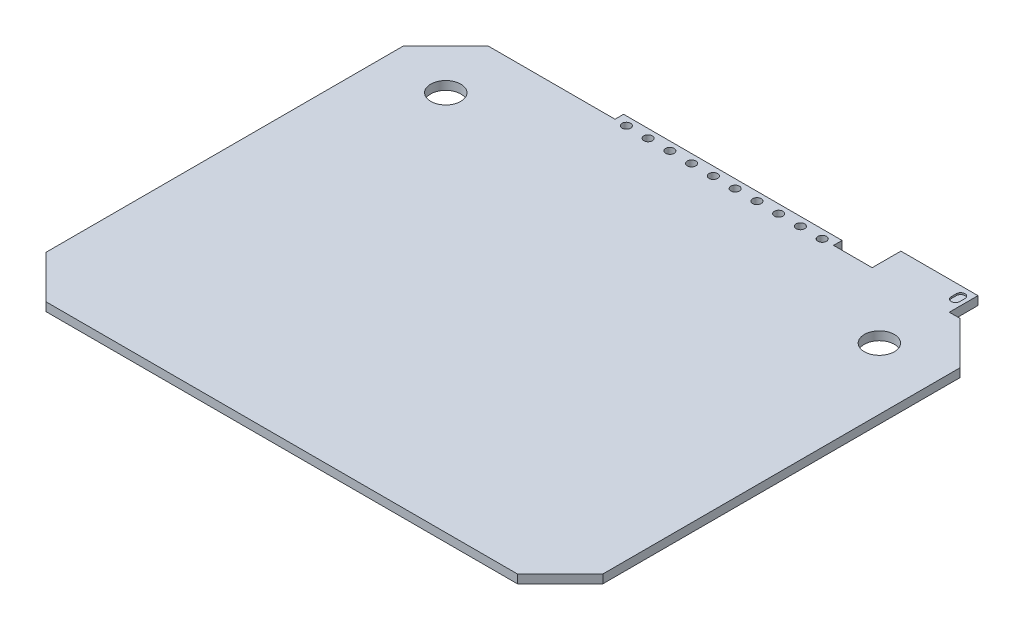
SolidWorks part; units mm, degrees
ref_plane "CL Y" through (0, 0, 0) normal (0, 0, 1) x (1, 0, 0)
ref_plane "PCBA Top" through (0, 0, 0) normal (0, 1, 0) x (1, 0, 0)
ref_plane "CL X" through (0, 0, 0) normal (1, 0, 0) x (0, 0, -1)
sketch "Sketch1" plane through (0, 0, 0) normal (0, 1, 0) x (1, 0, 0)
  line L0 (0, -50) -> (0, 50) construction
  line L1 (-32.5, 25.825) -> (32.5, 25.825)
  line L2 (-32.5, 25.825) -> (-32.5, -25.825)
  line L3 (-32.5, -25.825) -> (32.5, -25.825)
  line L4 (32.5, 25.825) -> (32.5, -25.825)
  line L5 (-50, 0) -> (50, 0) construction
  point P4 (0, 25.825)
  point P7 (32.5, 0)
  dimension "D1" = 65
  dimension "D2" = 51.65
extrude "Boss-Extrude1" add sketch "Sketch1" along normal blind 1
chamfer "Chamfer1" distance 5 angle 45 4 edges at (-32.5, 0.5, -25.825) (-32.5, 0.5, 25.825) (32.5, 0.5, -25.825) (32.5, 0.5, 25.825)
sketch "Sketch2" plane through (0, 0, 0) normal (0, 1, 0) x (1, 0, 0)
  line L0 (-25.3, 18.625) -> (25.3, 18.625) construction
  line L1 (0, -50) -> (0, 50) construction
  line L2 (27.5, 25.825) -> (-27.5, 25.825) construction
  circle A0 centre (-25.3, 18.625) radius 1.75
  circle A1 centre (25.3, 18.625) radius 1.75
  point P2 (0, 18.625)
  dimension "D3" = 3.5
  dimension "D1" = 7.2
  dimension "D2" = 50.6
extrude "Cut-Extrude2" cut sketch "Sketch2" along normal up to next
sketch "Sketch3" plane through (0, 1, 0) normal (0, 1, 0) x (1, 0, 0)
  line L0 (27.5, 25.825) -> (-27.5, 25.825) construction
  line L1 (-12.75, 26.825) -> (12.75, 26.825)
  line L2 (-12.75, 26.825) -> (-12.75, 25.825)
  line L3 (-12.75, 25.825) -> (12.75, 25.825)
  line L4 (12.75, 26.825) -> (12.75, 25.825)
  line L5 (0, -50) -> (0, 50) construction
  point P6 (0, 26.825)
  dimension "D1" = 25.5
  dimension "D2" = 1
extrude "Boss-Extrude3" add sketch "Sketch3" against normal up to surface (1 mm away) up to face at (-25.3, 0, -16.875)
sketch "Sketch4" plane through (0, 1, 0) normal (0, 1, 0) x (1, 0, 0)
  line L0 (-12.75, 25.825) -> (12.75, 25.825) construction
  line L1 (-1.27, 24.6659) -> (-1.27, 26.9841) construction
  line L2 (0, -50) -> (0, 50) construction
  circle A0 centre (-1.27, 25.825) radius 0.5
  dimension "D2" = 1
  dimension "D1" = 1.27
extrude "Cut-Extrude3" cut sketch "Sketch4" against normal up to next
pattern_linear "LPattern1" count 6 spacing 2.54 along (1, 0, 0) count 5 spacing 2.54 along (-1, 0, 0) of "Cut-Extrude3"
sketch "Sketch5" plane through (0, 1, 0) normal (0, 1, 0) x (1, 0, 0)
  line L0 (27.5, 25.825) -> (12.75, 25.825) construction
  line L1 (17.26, 29.175) -> (26.26, 29.175)
  line L2 (17.26, 29.175) -> (17.26, 25.825)
  line L3 (17.26, 25.825) -> (26.26, 25.825)
  line L4 (26.26, 29.175) -> (26.26, 25.825)
  line L6 (21.76, 29.175) -> (21.76, 35.5034) construction
  line L7 (0, -50) -> (0, 50) construction
  dimension "D1" = 9
  dimension "D2" = 3.35
  dimension "D3" = 21.76
extrude "Boss-Extrude4" add sketch "Sketch5" against normal up to surface (1 mm away) up to face at (11.43, 0, -25.325)
sketch "Sketch6" plane through (0, 1, 0) normal (0, 1, 0) x (1, 0, 0)
  line L0 (25.3, 28.115) -> (25.3, 27.515) construction
  line L1 (25.8, 28.115) -> (25.8, 27.515)
  line L2 (24.8, 28.115) -> (24.8, 27.515)
  line L3 (25.3, 18.625) -> (25.3, 31.5325) construction
  arc A0 (25.8, 28.115) -> (24.8, 28.115) centre (25.3, 28.115) ccw
  arc A1 (24.8, 27.515) -> (25.8, 27.515) centre (25.3, 27.515) ccw
  circle A2 centre (25.3, 18.625) radius 1.75 construction
  point P2 (25.3, 27.815)
  dimension "D1" = 9.19
  dimension "D2" = 1
  dimension "D3" = 0.6
extrude "Cut-Extrude4" cut sketch "Sketch6" against normal blind 0.2
